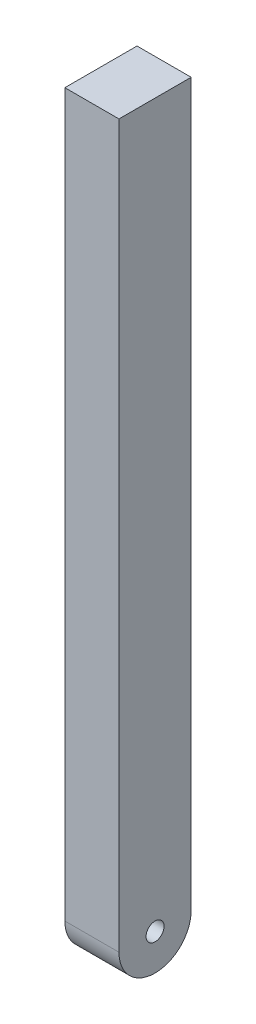
SolidWorks part; units mm, degrees
ref_plane "Plan de face" through (0, 0, 0) normal (0, 0, 1) x (1, 0, 0)
ref_plane "Plan de dessus" through (0, 0, 0) normal (0, 1, 0) x (1, 0, 0)
ref_plane "Plan de droite" through (0, 0, 0) normal (1, 0, 0) x (0, 0, -1)
sketch "Esquisse3" plane through (0, 0, 0) normal (1, 0, 0) x (0, 0, -1)
  line L1 (10, 100) -> (-10, 100)
  line L2 (10, 100) -> (10, -100)
  line L4 (-10, 100) -> (-10, -100)
  line L5 (10, 100) -> (-10, -100) construction
  line L6 (10, -100) -> (-10, 100) construction
  arc A0 (-10, -100) -> (10, -100) centre (0, -100) ccw
  circle A1 centre (0, -100) radius 2.5
  point P0 (0, 0)
  dimension "D3" = 20
  dimension "D4" = 5
  dimension "D1" = 200
  dimension "D2" = 20
extrude "BASE" add sketch "Esquisse3" along normal blind 15
